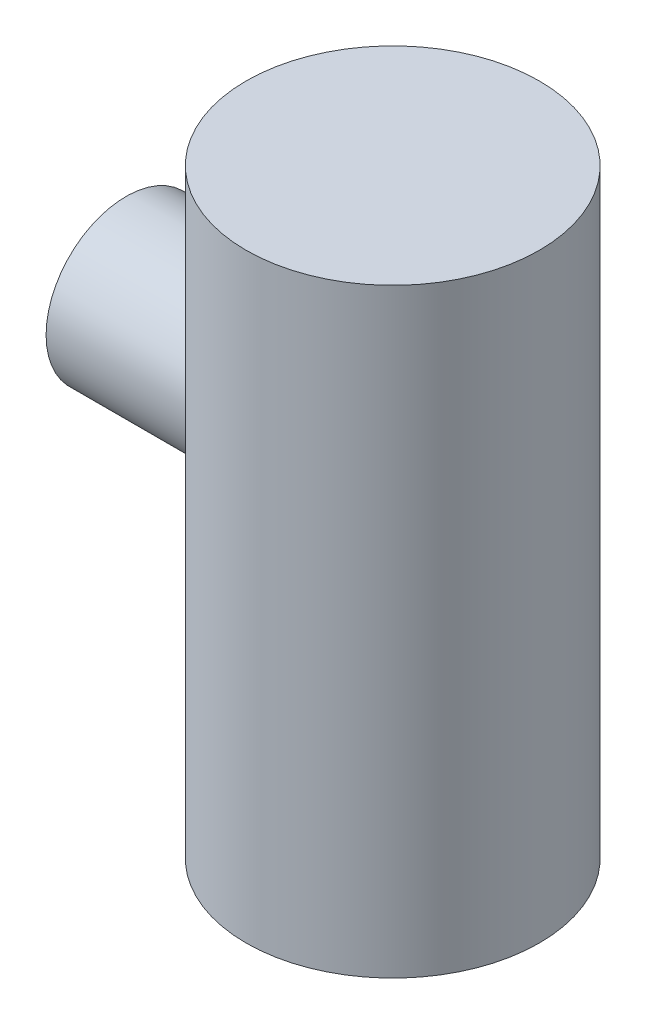
SolidWorks part; units mm, degrees
ref_plane "Front Plane" through (0, 0, 0) normal (0, 0, 1) x (1, 0, 0)
ref_plane "Top Plane" through (0, 0, 0) normal (0, 1, 0) x (1, 0, 0)
ref_plane "Right Plane" through (0, 0, 0) normal (1, 0, 0) x (0, 0, -1)
sketch "Sketch1" plane through (0, 0, 0) normal (0, 1, 0) x (1, 0, 0)
  circle A0 centre (0, 0) radius 27.94
  dimension "D1" = 55.88
extrude "Boss-Extrude1" add sketch "Sketch1" along normal blind 114.3
sketch "Sketch2" plane through (0, 0, 0) normal (0, 0, 1) x (1, 0, 0)
  line L0 (-43.6446, 28.575) -> (-14.9935, 28.575)
  line L1 (-14.9935, 28.575) -> (-14.9935, 25.4)
  line L2 (-14.9935, 25.4) -> (-43.6446, 25.4) construction
  line L3 (-43.6446, 25.4) -> (-43.6446, 28.575)
  line L4 (-27.94, 0) -> (27.94, 0) construction
  line L5 (-43.6446, 25.4) -> (-14.9935, 25.4)
  dimension "D1" = 3.175
  dimension "D2" = 25.4
revolve "inlet" cut sketch "Sketch2" angle 360 about L2
sketch "Sketch3" plane through (0, 0, 0) normal (0, -1, 0) x (1, 0, 0)
  circle A0 centre (0, 0) radius 3.175
  dimension "D1" = 6.35
extrude "outlet" cut sketch "Sketch3" against normal blind 25.4
sketch "Sketch4" plane through (0, 0, 0) normal (0, 0, 1) x (1, 0, 0)
  line L0 (-27.94, 0) -> (27.94, 0) construction
  line L1 (-50.8, 83.82) -> (0, 83.82)
  line L2 (-50.8, 83.82) -> (-50.8, 68.58)
  line L3 (-50.8, 68.58) -> (0, 68.58)
  line L4 (0, 83.82) -> (0, 68.58)
  dimension "D1" = 50.8
  dimension "D2" = 68.58
  dimension "D3" = 15.24
revolve "Revolve1" add sketch "Sketch4" angle 360 about L3
hole_wizard "1/2 NPT Tapped Hole1" positions "Sketch5" profile "Sketch6" size "1/2" standard "ANSI Inch"
sketch "Sketch5" plane through (-50.8, 0, 0) normal (-1, 0, 0) x (0, 0, 1)
  point P0 (0, 68.58)
sketch "Sketch6" plane through (-50.8, 68.58, 0) normal (0, 1, 0) x (0, 0, 1)
  line L0 (0, 0) -> (0, 27.9705)
  line L1 (8.9281, 22.606) -> (0, 27.9705)
  line L2 (-8.9281, 22.606) -> (0, 27.9705) construction
  line L3 (8.9281, 22.606) -> (8.9281, 13.462)
  line L4 (8.9281, 13.462) -> (10.2807, 13.462)
  line L5 (10.2807, 13.462) -> (10.6647, 0.635)
  line L6 (10.6647, 0.635) -> (11.2997, 0)
  line L7 (11.2997, 0) -> (0, 0)
  line L8 (0, -6.35) -> (0, 107.95) construction
  line L9 (-10.6647, 0.635) -> (-11.2997, 0) construction
  line L11 (-8.9281, 13.462) -> (-10.2807, 13.462) construction
  line L12 (-10.2807, 13.462) -> (-10.6647, 0.635) construction
  dimension "Tap Drill Dia." = 17.8562
  dimension "Tap Drill Depth" = 22.606
  dimension "Thread Dia." = 21.3295
  dimension "Thread Angle" = 3.43
  dimension "Thread Depth" = 13.462
  dimension "C'Sink Dia." = 22.5995
  dimension "C'Sink Angle" = 90
  dimension "Drill Angle" = 118
